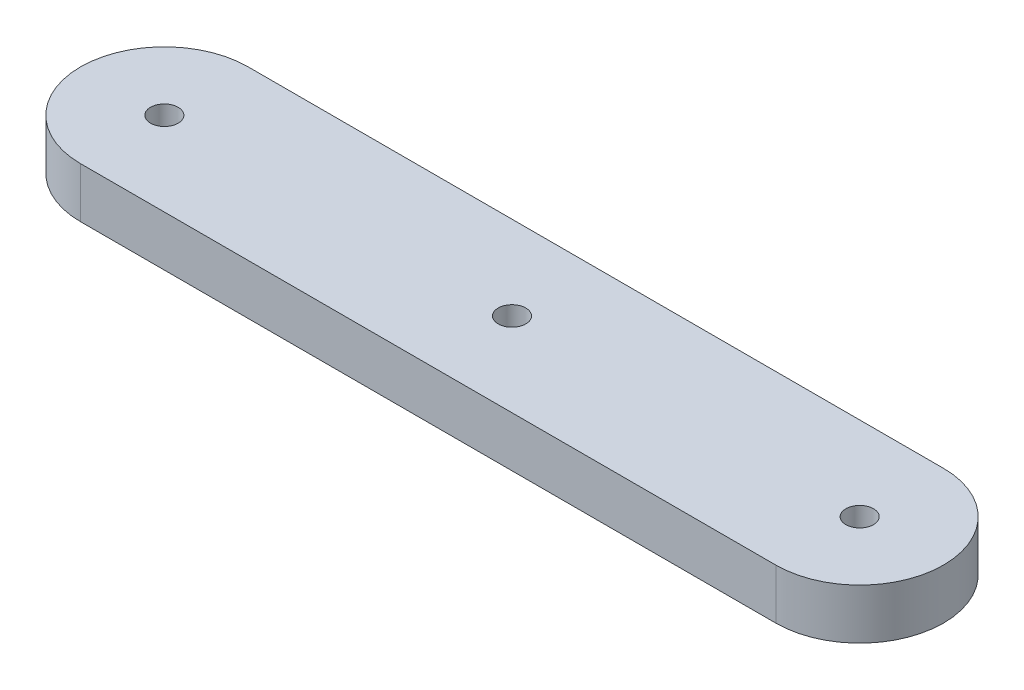
SolidWorks part; units mm, degrees
ref_plane "Front Plane" through (0, 0, 0) normal (0, 0, 1) x (1, 0, 0)
ref_plane "Top Plane" through (0, 0, 0) normal (0, 1, 0) x (1, 0, 0)
ref_plane "Right Plane" through (0, 0, 0) normal (1, 0, 0) x (0, 0, -1)
sketch "Sketch1" plane through (0, 0, 0) normal (0, 1, 0) x (1, 0, 0)
  line L0 (-41.48, 0) -> (41.48, 0) construction
  line L1 (-41.48, 10) -> (41.48, 10)
  line L2 (-41.48, -10) -> (41.48, -10)
  line L3 (0, 58.671) -> (0, -70.3711) construction
  arc A0 (-41.48, 10) -> (-41.48, -10) centre (-41.48, 0) ccw
  arc A1 (41.48, -10) -> (41.48, 10) centre (41.48, 0) ccw
  circle A2 centre (-41.48, 0) radius 1.65
  circle A3 centre (41.48, 0) radius 1.65
  circle A4 centre (0, 0) radius 1.65
  point P3 (0, 0)
  dimension "D3" = 3.3
  dimension "D4" = 3.3
  dimension "D1" = 82.96
  dimension "D2" = 20
extrude "Boss-Extrude1" add sketch "Sketch1" along normal blind 6
